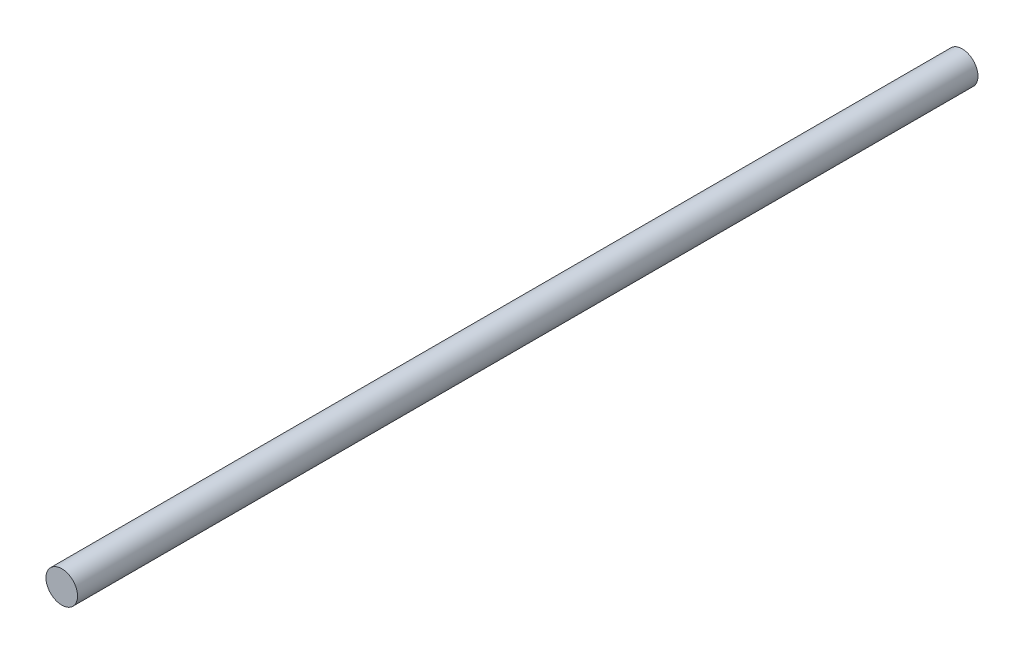
SolidWorks part; units mm, degrees
ref_plane "Front Plane" through (0, 0, 0) normal (0, 0, 1) x (1, 0, 0)
ref_plane "Top Plane" through (0, 0, 0) normal (0, 1, 0) x (1, 0, 0)
ref_plane "Right Plane" through (0, 0, 0) normal (1, 0, 0) x (0, 0, -1)
sketch "Sketch1" plane through (0, 0, 0) normal (0, 0, 1) x (1, 0, 0)
  circle A0 centre (0, 0) radius 10
  dimension "D1" = 20
extrude "Boss-Extrude1" add sketch "Sketch1" along normal blind 570
